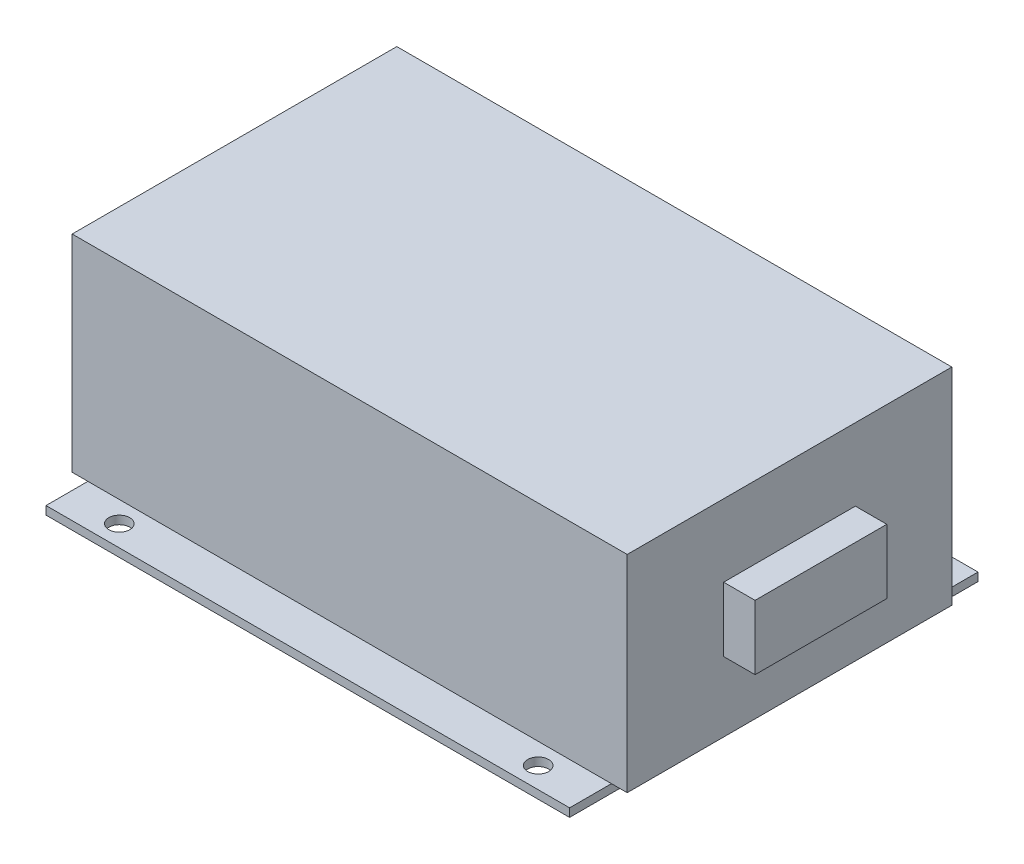
SolidWorks part; units mm, degrees
ref_plane "Front Plane" through (0, 0, 0) normal (0, 0, 1) x (1, 0, 0)
ref_plane "Top Plane" through (0, 0, 0) normal (0, 1, 0) x (1, 0, 0)
ref_plane "Right Plane" through (0, 0, 0) normal (1, 0, 0) x (0, 0, -1)
sketch "Sketch1" plane through (0, 0, 0) normal (0, 1, 0) x (1, 0, 0)
  line L1 (-50, -39) -> (50, -39)
  line L2 (-50, -39) -> (-50, 39)
  line L3 (-50, 39) -> (50, 39)
  line L4 (50, -39) -> (50, 39)
  line L5 (-50, -39) -> (50, 39) construction
  line L6 (-50, 39) -> (50, -39) construction
  circle A0 centre (-40, 35) radius 2
  circle A1 centre (40, 35) radius 2
  circle A2 centre (-40, -35) radius 2
  circle A3 centre (40, -35) radius 2
  point P0 (0, 0)
  dimension "D3" = 4
  dimension "D1" = 78
  dimension "D2" = 100
  dimension "D4" = 10
  dimension "D5" = 10
  dimension "D6" = 4
  dimension "D7" = 4
extrude "Boss-Extrude1" add sketch "Sketch1" along normal blind 1.5875
sketch "Sketch2" plane through (0, 1.5875, 0) normal (0, 1, 0) x (-1, 0, 0)
  line L1 (53, 31) -> (-53, 31)
  line L2 (53, 31) -> (53, -31)
  line L3 (53, -31) -> (-53, -31)
  line L4 (-53, 31) -> (-53, -31)
  line L5 (53, 31) -> (-53, -31) construction
  line L6 (53, -31) -> (-53, 31) construction
  point P0 (0, 0)
  dimension "D1" = 106
  dimension "D2" = 62
extrude "Boss-Extrude2" add sketch "Sketch2" along normal blind 39.4125
sketch "Sketch3" plane through (53, 0, 0) normal (1, 0, 0) x (0, 0, -1)
  line L1 (-12.5784, 27.1966) -> (12.5784, 27.1966)
  line L2 (-12.5784, 27.1966) -> (-12.5784, 14.8999)
  line L3 (-12.5784, 14.8999) -> (12.5784, 14.8999)
  line L4 (12.5784, 27.1966) -> (12.5784, 14.8999)
  line L5 (-12.5784, 27.1966) -> (12.5784, 14.8999) construction
  line L6 (-12.5784, 14.8999) -> (12.5784, 27.1966) construction
  point P0 (0, 21.0483)
extrude "Boss-Extrude3" add sketch "Sketch3" along normal blind 6
